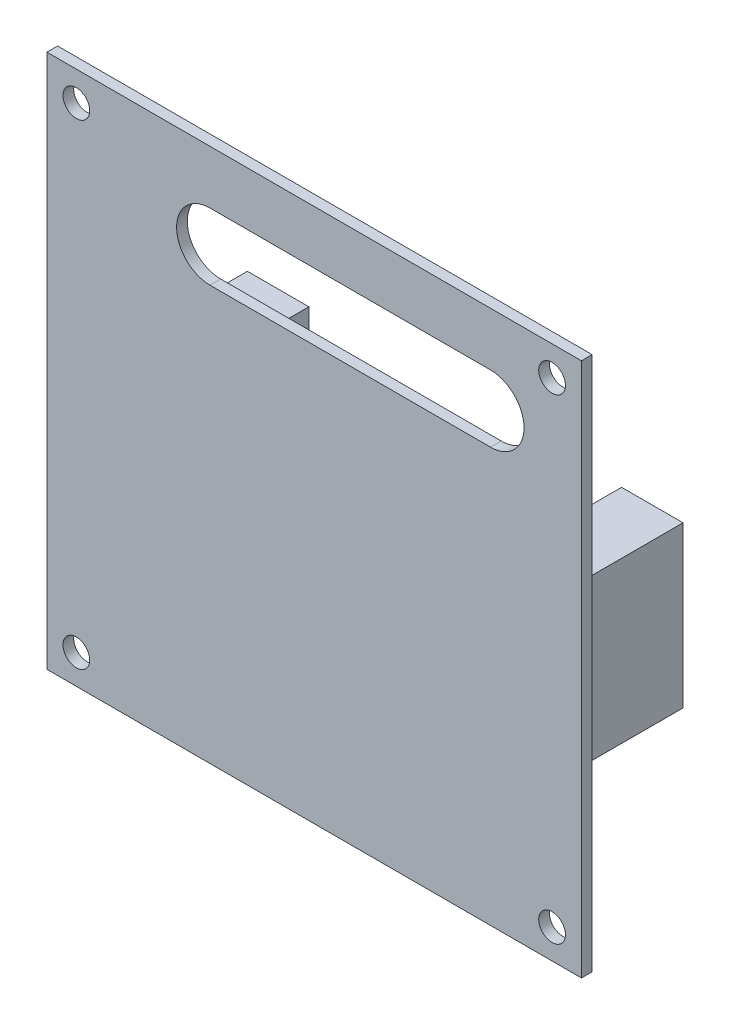
SolidWorks part; units mm, degrees
ref_plane "Front Plane" through (0, 0, 0) normal (0, 0, 1) x (1, 0, 0)
ref_plane "Top Plane" through (0, 0, 0) normal (0, 1, 0) x (1, 0, 0)
ref_plane "Right Plane" through (0, 0, 0) normal (1, 0, 0) x (0, 0, -1)
sketch "Sketch1" plane through (0, 0, 0) normal (0, 0, 1) x (1, 0, 0)
  line L0 (-19.9374, -20.069) -> (20.0626, -20.069)
  line L1 (20.0626, -20.069) -> (20.0626, 19.931)
  line L2 (20.0626, 19.931) -> (-19.9374, 19.931)
  line L3 (-19.9374, 19.931) -> (-19.9374, -20.069)
  circle A0 centre (-17.7374, -17.869) radius 1
  circle A1 centre (-17.7374, 17.731) radius 1
  circle A2 centre (17.8626, 17.731) radius 1
  circle A3 centre (-17.7374, -17.869) radius 1
  circle A4 centre (17.8626, -17.869) radius 1
extrude "Boss-Extrude1" add sketch "Sketch1" along normal blind 0.8 contours L2 L3 L0 L1 A4 A2 A1 A0
sketch "Sketch4" plane through (0, 0, 0.8) normal (0, 0, 1) x (1, 0, 0)
  line L0 (-13.1374, 19.931) -> (-13.1374, -20.069) construction
  line L2 (20.0626, 19.931) -> (-19.9374, 19.931) construction
  line L3 (-19.9374, -20.069) -> (20.0626, -20.069) construction
  line L4 (-13.1374, -20.069) -> (10.2626, -20.069) construction
  line L5 (10.2626, -20.069) -> (10.2626, 19.931) construction
  line L6 (-19.9374, 19.931) -> (-19.9374, -20.069) construction
  line L7 (20.0626, -20.069) -> (20.0626, 19.931) construction
  line L8 (20.0626, 0.431) -> (-19.9374, 0.431) construction
  line L9 (20.0626, 0.431) -> (10.2626, 0.431) construction
  line L10 (10.2626, 0.431) -> (-13.1374, 0.431) construction
  line L11 (-13.1374, 0.431) -> (-19.9374, 0.431) construction
  line L13 (10.2626, 0.431) -> (14.8626, 0.431)
  line L14 (10.2626, 0.431) -> (10.2626, -11.569)
  line L15 (10.2626, -11.569) -> (14.8626, -11.569)
  line L16 (14.8626, 0.431) -> (14.8626, -11.569)
  line L17 (-13.1374, 0.431) -> (-17.7374, 0.431)
  line L18 (-13.1374, 0.431) -> (-13.1374, -11.569)
  line L19 (-13.1374, -11.569) -> (-17.7374, -11.569)
  line L20 (-17.7374, 0.431) -> (-17.7374, -11.569)
  dimension "D1" = 6.8
  dimension "D2" = 9.8
  dimension "D3" = 20.5
  dimension "D4" = 12
  dimension "D5" = 4.6
  dimension "D6" = 12
  dimension "D7" = 4.6
extrude "Boss-Extrude2" add sketch "Sketch4" against normal blind 12.8
ref_plane "Plane1" through (0, 0.431, 0) normal (0, 1, 0) x (1, 0, 0)
sketch "Sketch5" plane through (0, 0.431, 0) normal (0, 1, 0) x (1, 0, 0)
  line L0 (-17.7374, 12) -> (-13.1374, 0) construction
  line L1 (-13.1374, 0) -> (-13.1374, 12) construction
  line L2 (-13.1374, 12) -> (-17.7374, 0) construction
  line L3 (-17.7374, 0) -> (-17.7374, 6.2) construction
  line L4 (-17.7374, 12) -> (-17.7374, 0) construction
  line L5 (-17.7374, 6.2) -> (-15.4374, 6.2) construction
  line L6 (10.2626, 0) -> (10.2626, 6.2) construction
  line L7 (10.2626, 12) -> (10.2626, 0) construction
  line L8 (10.2626, 6.2) -> (12.5626, 6.2) construction
  circle A0 centre (-15.4374, 6.2) radius 0.6
  circle A1 centre (12.5626, 6.2) radius 0.6
  dimension "D5" = 1.2
  dimension "D6" = 1.2
  dimension "D1" = 2.3
  dimension "D2" = 6.2
  dimension "D3" = 6.2
  dimension "D4" = 2.3
extrude "Cut-Extrude1" cut sketch "Sketch5" against normal blind 6
sketch "Sketch6" plane through (0, 0, 0) normal (0, 0, -1) x (-1, 0, 0)
  line L0 (-10.2626, 0.431) -> (-10.2626, 19.931) construction
  line L1 (-20.0626, 19.931) -> (19.9374, 19.931) construction
  line L2 (-10.2626, 10.931) -> (19.9374, 10.931) construction
  line L3 (19.9374, 19.931) -> (19.9374, -20.069) construction
  line L4 (7.7374, 10.931) -> (-13.2626, 10.931) construction
  line L6 (7.7374, 10.931) -> (-13.2626, 10.931)
  line L7 (7.7374, 10.931) -> (7.7374, 15.931) construction
  line L8 (7.7374, 15.931) -> (-13.2626, 15.931)
  line L9 (-13.2626, 10.931) -> (-13.2626, 15.931) construction
  circle A0 centre (7.7374, 13.431) radius 2.5 construction
  circle A1 centre (-13.2626, 13.431) radius 2.5 construction
  arc A2 (-13.2626, 10.931) -> (-13.2626, 15.931) centre (-13.2626, 13.431) cw
  arc A3 (7.7374, 10.931) -> (7.7374, 15.931) centre (7.7374, 13.431) ccw
  dimension "D1" = 9
  dimension "D2" = 21
  dimension "D3" = 3
  dimension "D4" = 5
extrude "Cut-Extrude2" cut sketch "Sketch6" against normal blind 6
